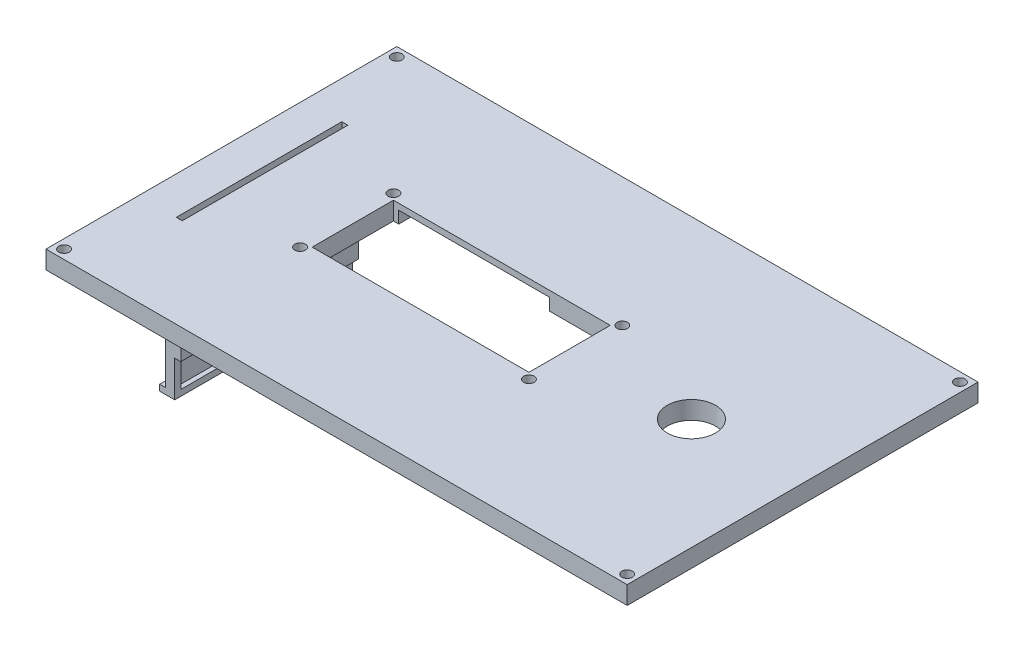
SolidWorks part; units mm, degrees
ref_plane "Front Plane" through (0, 0, 0) normal (0, 0, 1) x (1, 0, 0)
ref_plane "Top Plane" through (0, 0, 0) normal (0, 1, 0) x (1, 0, 0)
ref_plane "Right Plane" through (0, 0, 0) normal (1, 0, 0) x (0, 0, -1)
sketch "Sketch1" plane through (0, 0, 0) normal (0, 1, 0) x (1, 0, 0)
  line L1 (-73.6202, 41.1716) -> (119.3798, 41.1716)
  line L2 (-73.6202, 41.1716) -> (-73.6202, -75.3284)
  line L3 (-73.6202, -75.3284) -> (119.3798, -75.3284)
  line L4 (119.3798, 41.1716) -> (119.3798, -75.3284)
  line L9 (-29.9882, -3.5784) -> (42.0118, -3.5784)
  line L10 (-29.9882, -3.5784) -> (-29.9882, -30.5784)
  line L11 (-29.9882, -30.5784) -> (42.0118, -30.5784)
  line L12 (42.0118, -3.5784) -> (42.0118, -30.5784)
  line L13 (-48.3313, 10.4216) -> (-46.3313, 10.4216)
  line L14 (-48.3313, 10.4216) -> (-48.3313, -44.5784)
  line L15 (-48.3313, -44.5784) -> (-46.3313, -44.5784)
  line L16 (-46.3313, 10.4216) -> (-46.3313, -44.5784)
  circle A0 centre (-31.9882, -1.5784) radius 1.75
  circle A1 centre (-31.9882, -32.5784) radius 1.75
  circle A2 centre (44.0118, -1.5784) radius 1.75
  circle A3 centre (44.0118, -32.5784) radius 1.75
  circle A4 centre (-70.6202, -72.3284) radius 1.75
  circle A5 centre (-70.6202, 38.1716) radius 1.75
  circle A6 centre (116.3798, -72.3284) radius 1.75
  circle A7 centre (116.3798, 38.1716) radius 1.75
  circle A8 centre (82.4507, -17.0784) radius 8
  dimension "D12" = 2
  dimension "D3" = 16
  dimension "D1" = 193
  dimension "D2" = 116.5
  dimension "D4" = 58.25
  dimension "D6" = 72
  dimension "D7" = 27
  dimension "D8" = 44.75
  dimension "D9" = 55
  dimension "D10" = 2
  dimension "D11" = 30.75
  dimension "D13" = 2
  dimension "D14" = 2
  dimension "D15" = 2
  dimension "D16" = 3
  dimension "D17" = 3
  dimension "D18" = 3
  dimension "D19" = 3
extrude "Boss-Extrude1" add sketch "Sketch1" along normal blind 6
sketch "Sketch3" plane through (0, 0, 0) normal (0, -1, 0) x (1, 0, 0)
  line L0 (-73.6202, 75.3284) -> (119.3798, 75.3284) construction
  line L1 (-67.6202, 69.3284) -> (-57.6202, 69.3284)
  line L2 (-67.6202, 69.3284) -> (-67.6202, 59.3284)
  line L3 (-67.6202, 59.3284) -> (-57.6202, 59.3284)
  line L4 (-57.6202, 69.3284) -> (-57.6202, 59.3284)
  line L5 (-73.6202, -41.1716) -> (-73.6202, 75.3284) construction
  line L6 (-67.6202, -25.1716) -> (-57.6202, -25.1716)
  line L7 (-67.6202, -25.1716) -> (-67.6202, -35.1716)
  line L8 (-67.6202, -35.1716) -> (-57.6202, -35.1716)
  line L9 (-57.6202, -25.1716) -> (-57.6202, -35.1716)
  line L10 (119.3798, -41.1716) -> (-73.6202, -41.1716) construction
  line L11 (103.3798, -25.1716) -> (113.3798, -25.1716)
  line L12 (103.3798, -25.1716) -> (103.3798, -35.1716)
  line L13 (103.3798, -35.1716) -> (113.3798, -35.1716)
  line L14 (113.3798, -25.1716) -> (113.3798, -35.1716)
  line L15 (119.3798, 75.3284) -> (119.3798, -41.1716) construction
  line L16 (103.3798, 69.3284) -> (113.3798, 69.3284)
  line L17 (103.3798, 69.3284) -> (103.3798, 59.3284)
  line L18 (103.3798, 59.3284) -> (113.3798, 59.3284)
  line L19 (113.3798, 69.3284) -> (113.3798, 59.3284)
  dimension "D1" = 10
  dimension "D2" = 10
  dimension "D3" = 6
  dimension "D4" = 6
  dimension "D5" = 6
  dimension "D6" = 6
  dimension "D7" = 6
  dimension "D8" = 6
  dimension "D9" = 6
  dimension "D10" = 6
  dimension "D11" = 10
  dimension "D12" = 10
  dimension "D13" = 10
  dimension "D14" = 10
  dimension "D15" = 10
  dimension "D16" = 10
extrude "Boss-Extrude3" add sketch "Sketch3" along normal blind 10
sketch "Sketch5" plane through (0, 0, 0) normal (0, -1, 0) x (1, 0, 0)
  line L1 (-48.3313, 44.5784) -> (-46.3313, 44.5784)
  line L2 (-48.3313, 44.5784) -> (-48.3313, -10.4216)
  line L3 (-48.3313, -10.4216) -> (-46.3313, -10.4216)
  line L4 (-46.3313, 44.5784) -> (-46.3313, -10.4216)
extrude "Boss-Extrude4" add sketch "Sketch5" against normal blind 6
sketch "Sketch6" plane through (0, -10, 0) normal (0, -1, 0) x (1, 0, 0)
  line L1 (-67.6202, 69.3284) -> (113.3798, 69.3284)
  line L2 (-67.6202, 69.3284) -> (-67.6202, -35.1716)
  line L3 (-67.6202, -35.1716) -> (113.3798, -35.1716)
  line L4 (113.3798, 69.3284) -> (113.3798, -35.1716)
extrude "Cut-Extrude1" cut sketch "Sketch6" against normal blind 4
sketch "Sketch7" plane through (0, 0, 0) normal (0, -1, 0) x (1, 0, 0)
  line L0 (119.3798, -41.1716) -> (-73.6202, -41.1716) construction
  line L1 (-62.6202, 44.5784) -> (-61.1202, 44.5784)
  line L2 (-62.6202, 44.5784) -> (-62.6202, -10.4216)
  line L3 (-62.6202, -10.4216) -> (-61.1202, -10.4216)
  line L4 (-61.1202, 44.5784) -> (-61.1202, -10.4216)
  line L6 (-73.6202, -41.1716) -> (-73.6202, 75.3284) construction
  dimension "D1" = 55
  dimension "D2" = 1.5
  dimension "D3" = 30.75
  dimension "D4" = 11
extrude "Boss-Extrude5" add sketch "Sketch7" along normal blind 44.75
sketch "Sketch8" plane through (0, 0, 0) normal (0, -1, 0) x (1, 0, 0)
  line L1 (-61.1202, 44.5784) -> (-59.1202, 44.5784)
  line L2 (-61.1202, 44.5784) -> (-61.1202, -10.4216)
  line L3 (-61.1202, -10.4216) -> (-59.1202, -10.4216)
  line L4 (-59.1202, 44.5784) -> (-59.1202, -10.4216)
  dimension "D1" = 55
  dimension "D2" = 2
extrude "Cut-Extrude2" cut sketch "Sketch8" against normal blind 42.25
sketch "Sketch10" plane through (0, 0, 0) normal (0, -1, 0) x (1, 0, 0)
  line L0 (42.0118, 30.5784) -> (42.0118, 3.5784) construction
  line L1 (42.0118, 26.5784) -> (48.0118, 26.5784)
  line L2 (42.0118, 26.5784) -> (42.0118, 7.5784)
  line L3 (42.0118, 7.5784) -> (48.0118, 7.5784)
  line L4 (48.0118, 26.5784) -> (48.0118, 7.5784)
  line L5 (-73.6202, 75.3284) -> (119.3798, 75.3284) construction
  dimension "D1" = 19
  dimension "D2" = 48.75
  dimension "D3" = 6
extrude "Cut-Extrude3" cut sketch "Sketch10" against normal blind 4 contours L4 L3 L2 L1
fillet "Fillet3" radius 3 16 edges at (-62.6202, -6, -35.1716) (-67.6202, -6, -30.1716) (-62.6202, -6, -25.1716) (-57.6202, -6, -30.1716) (-67.6202, -6, 64.3284) (-62.6202, -6, 69.3284) (-57.6202, -6, 64.3284) (-62.6202, -6, 59.3284) (108.3798, -6, 69.3284) (113.3798, -6, 64.3284) (108.3798, -6, 59.3284) (103.3798, -6, 64.3284) (108.3798, -6, -25.1716) (113.3798, -6, -30.1716) (108.3798, -6, -35.1716) (103.3798, -6, -30.1716)
sketch "Sketch12" plane through (-61.1202, 0, 0) normal (1, 0, 0) x (0, 0, -1)
  line L0 (10.4216, -44.75) -> (10.4216, 0) construction
  line L1 (-44.5784, -44.75) -> (10.4216, -44.75)
  line L2 (-44.5784, -44.75) -> (-44.5784, -42.75)
  line L3 (-44.5784, -42.75) -> (10.4216, -42.75)
  line L4 (10.4216, -44.75) -> (10.4216, -42.75)
  dimension "D1" = 2
extrude "Boss-Extrude6" add sketch "Sketch12" along normal blind 1.5
sketch "Sketch14" plane through (0, 0, -10.4216) normal (0, 0, -1) x (-1, 0, 0)
  line L1 (59.6202, -44.75) -> (62.6202, -44.75)
  line L2 (59.6202, -44.75) -> (59.6202, 0)
  line L3 (59.6202, 0) -> (62.6202, 0)
  line L4 (62.6202, -44.75) -> (62.6202, 0)
  point P0 (59.6202, -44.75)
  point P1 (62.6202, 0)
extrude "Boss-Extrude7" add sketch "Sketch14" along normal blind 2
sketch "Sketch15" plane through (0, 0, 44.5784) normal (0, 0, 1) x (1, 0, 0)
  line L1 (-62.6202, 0) -> (-59.6202, 0)
  line L2 (-62.6202, 0) -> (-62.6202, -44.75)
  line L3 (-62.6202, -44.75) -> (-59.6202, -44.75)
  line L4 (-59.6202, 0) -> (-59.6202, -44.75)
  point P0 (-59.6202, -44.75)
  point P1 (-62.6202, 0)
extrude "Boss-Extrude8" add sketch "Sketch15" along normal blind 2
sketch "Sketch16" plane through (-62.6202, 0, 0) normal (-1, 0, 0) x (0, 0, 1)
  line L0 (46.5784, 0) -> (-12.4216, 0) construction
  line L2 (-10.4216, 0) -> (-10.4216, -42.75)
  line L3 (-10.4216, -42.75) -> (46.5784, -42.75)
  line L5 (46.5784, 0) -> (46.5784, -44.75) construction
  line L6 (-12.4216, -44.75) -> (-12.4216, 0) construction
  line L7 (46.5784, -44.75) -> (-12.4216, -44.75) construction
  line L8 (-10.4216, 0) -> (-12.4216, 0)
  line L9 (-12.4216, 0) -> (-12.4216, -44.75)
  line L10 (-12.4216, -44.75) -> (46.5784, -44.75)
  line L11 (46.5784, -44.75) -> (46.5784, -42.75)
  dimension "D1" = 2
  dimension "D2" = 2
extrude "Boss-Extrude9" add sketch "Sketch16" along normal blind 2 contours L2 L3 L11 L10 L9 L8
sketch "Sketch18" plane through (-59.6202, 0, 0) normal (1, 0, 0) x (0, 0, -1)
  line L0 (-46.5784, -44.75) -> (-46.5784, 0) construction
  line L1 (-46.5784, 0) -> (-26.5784, 0)
  line L2 (-46.5784, 0) -> (-46.5784, -32.75)
  line L3 (-46.5784, -32.75) -> (-26.5784, -32.75)
  line L4 (12.4216, 0) -> (12.4216, -32.75)
  line L5 (12.4216, 0) -> (12.4216, -44.75) construction
  line L6 (-46.5784, -44.75) -> (12.4216, -44.75) construction
  line L7 (-75.3284, 0) -> (41.1716, 0) construction
  line L8 (-26.5784, -32.75) -> (-26.5784, 0)
  line L9 (-7.5784, -32.75) -> (-7.5784, 0)
  line L10 (-7.5784, -32.75) -> (12.4216, -32.75)
  line L11 (-7.5784, 0) -> (12.4216, 0)
  dimension "D1" = 12
  dimension "D2" = 0
  dimension "D3" = 20
  dimension "D4" = 20
extrude "Boss-Extrude10" add sketch "Sketch18" along normal blind 2
sketch "Sketch19" plane through (0, 0, 0) normal (0, -1, 0) x (1, 0, 0)
  line L0 (-29.9882, 30.5784) -> (42.0118, 30.5784) construction
  line L1 (-28.2382, 35.5784) -> (21.7618, 35.5784)
  line L2 (-28.2382, 35.5784) -> (-28.2382, -1.4216)
  line L3 (-28.2382, -1.4216) -> (21.7618, -1.4216)
  line L4 (21.7618, 35.5784) -> (21.7618, -1.4216)
  line L5 (42.0118, 3.5784) -> (-29.9882, 3.5784) construction
  circle A0 centre (-31.9882, 32.5784) radius 1.75 construction
  point P8 (-30.2382, 32.5784)
  dimension "D1" = 50
  dimension "D2" = 5
  dimension "D3" = 5
  dimension "D4" = 2
extrude "Cut-Extrude7" cut sketch "Sketch19" against normal blind 4
